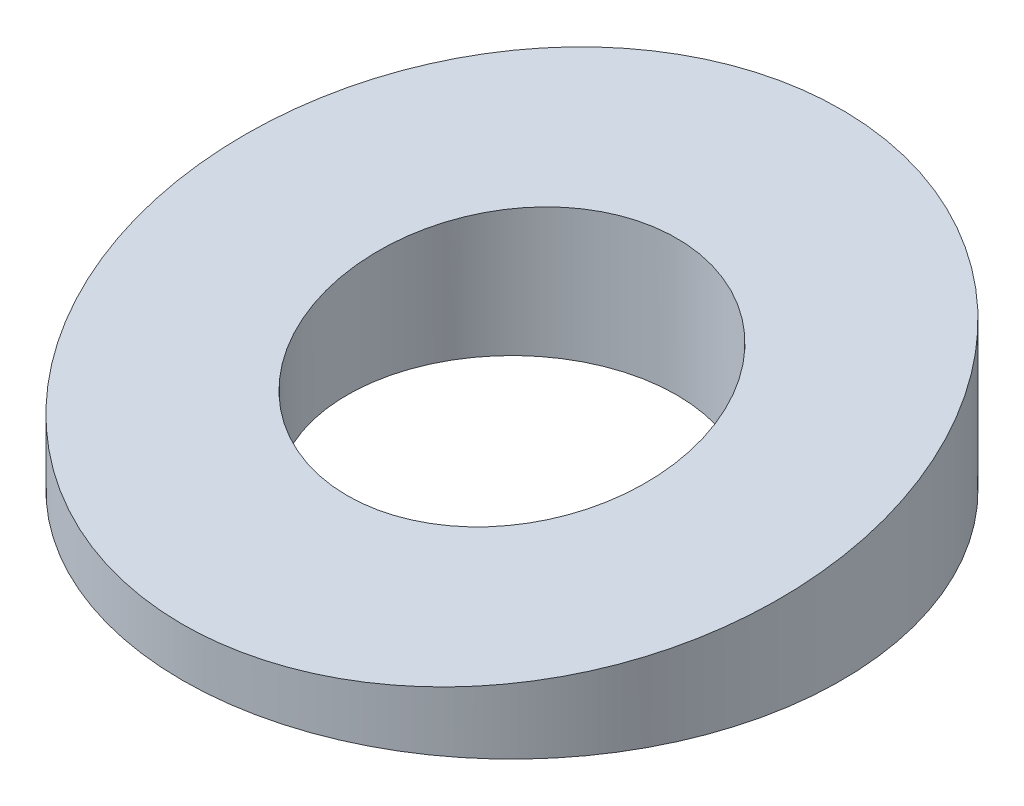
SolidWorks part; units mm, degrees
ref_plane "Front Plane" through (0, 0, 0) normal (0, 0, 1) x (1, 0, 0)
ref_plane "Top Plane" through (0, 0, 0) normal (0, 1, 0) x (1, 0, 0)
ref_plane "Right Plane" through (0, 0, 0) normal (1, 0, 0) x (0, 0, -1)
sketch "Sketch1" plane through (0, 0, 0) normal (0, 1, 0) x (1, 0, 0)
  circle A0 centre (0, 0) radius 2
  circle A1 centre (0, 0) radius 4
  dimension "D1" = 4
  dimension "D2" = 2
extrude "Boss-Extrude1" add sketch "Sketch1" along normal blind 2
sketch "Sketch2" plane through (0, 0, 0) normal (1, 0, 0) x (0, 0, -1)
  line L0 (4, 2) -> (-4, 0.5894)
  line L1 (-4, 2) -> (-4, 0) construction
  line L2 (4, 2) -> (-4, 2) construction
  line L4 (-4, 0.5894) -> (4, 0.5894)
  line L5 (-4, 0.5894) -> (-4, 2)
  line L6 (-4, 2) -> (4, 2)
  line L7 (4, 0.5894) -> (4, 2)
  dimension "D1" = 10
extrude "Cut-Extrude1" cut sketch "Sketch2" against normal blind 10 and the other way blind 10 contours L6 L5 L0
